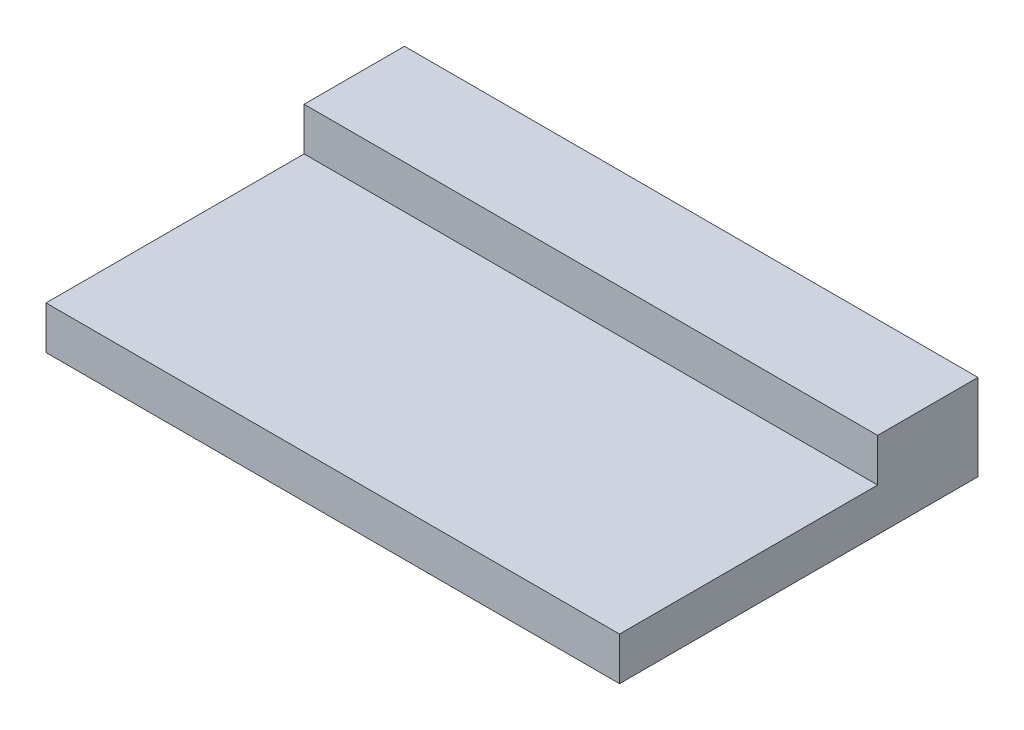
SolidWorks part; units mm, degrees
ref_plane "Front Plane" through (0, 0, 0) normal (0, 0, 1) x (1, 0, 0)
ref_plane "Top Plane" through (0, 0, 0) normal (0, 1, 0) x (1, 0, 0)
ref_plane "Right Plane" through (0, 0, 0) normal (1, 0, 0) x (0, 0, -1)
sketch "Sketch1" plane through (0, 0, 0) normal (0, 1, 0) x (1, 0, 0)
  line L1 (0, 0) -> (40, 0)
  line L2 (0, 0) -> (0, 25)
  line L3 (0, 25) -> (40, 25)
  line L4 (40, 0) -> (40, 25)
  dimension "D1" = 25
  dimension "D2" = 40
extrude "Boss-Extrude1" add sketch "Sketch1" along normal blind 3
sketch "Sketch2" plane through (0, 3, 0) normal (0, 1, 0) x (1, 0, 0)
  line L0 (40, 0) -> (40, 25) construction
  line L1 (0, 25) -> (40, 25)
  line L2 (0, 25) -> (0, 18)
  line L3 (0, 18) -> (40, 18)
  line L4 (40, 25) -> (40, 18)
  dimension "D1" = 7
extrude "Boss-Extrude2" add sketch "Sketch2" along normal blind 3
